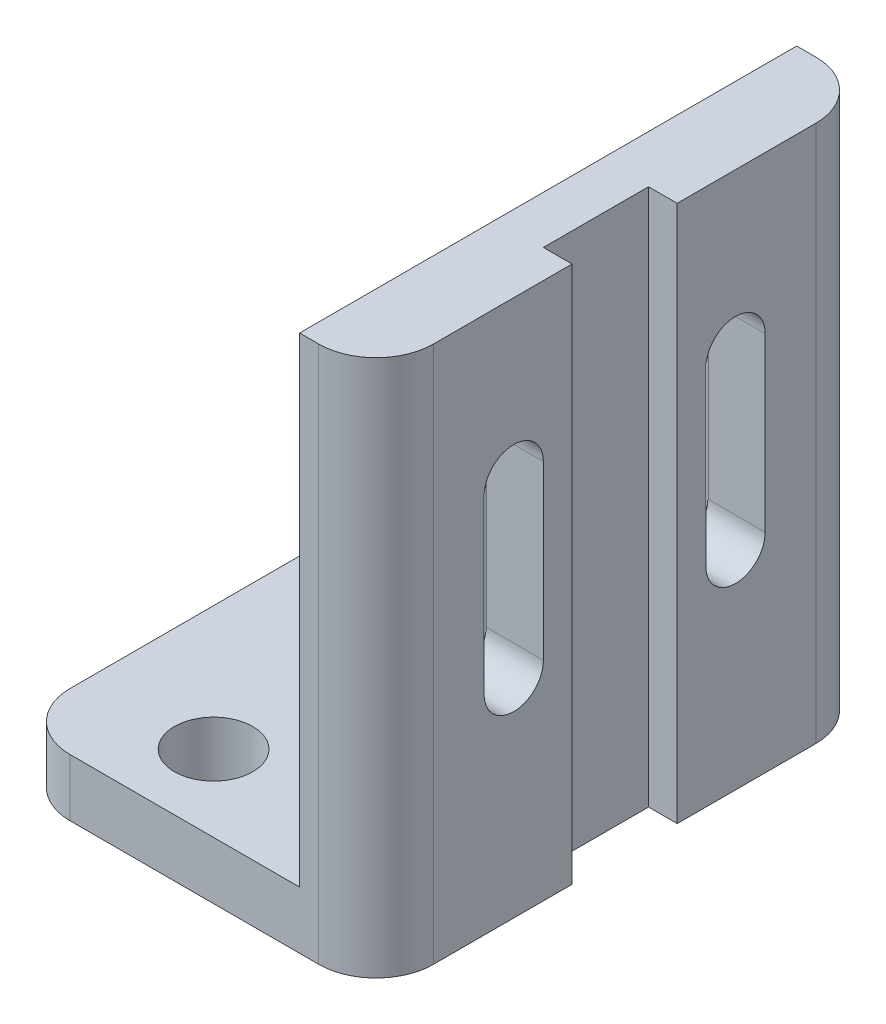
SolidWorks part; units mm, degrees
ref_plane "Front Plane" through (0, 0, 0) normal (0, 0, 1) x (1, 0, 0)
ref_plane "Top Plane" through (0, 0, 0) normal (0, 1, 0) x (1, 0, 0)
ref_plane "Right Plane" through (0, 0, 0) normal (1, 0, 0) x (0, 0, -1)
sketch "ProfileSketch1" plane through (0, 0, 0) normal (0, 0, 1) x (1, 0, 0)
  line L0 (0, 0) -> (19, 0)
  line L1 (19, 0) -> (19, 28.1)
  line L2 (19, 28.1) -> (15, 28.1)
  line L3 (15, 28.1) -> (15, 3)
  line L4 (15, 3) -> (0, 3)
  line L5 (0, 3) -> (0, 0)
  dimension "D1" = 28.1
  dimension "D3" = 3
  dimension "D4" = 4
  dimension "D2" = 15
extrude "Boss-Extrude1" add sketch "ProfileSketch1" along normal blind 26
sketch "BLTouchProbeMountHolesSketch2" plane through (0, 3, 0) normal (0, 1, 0) x (1, 0, 0)
  line L0 (15, -26) -> (0, -26) construction
  line L2 (15, -26) -> (15, 0) construction
  circle A0 centre (6.5, -4) radius 2.05
  circle A1 centre (6.5, -22) radius 2.05
  dimension "D4" = 4.1
  dimension "D1" = 18
  dimension "D2" = 4
  dimension "D3" = 8.5
extrude "BLTouchProbeMountHolesCut-Extrude1" cut sketch "BLTouchProbeMountHolesSketch2" against normal through all
sketch "ProbeSlidingMountSketch4" plane through (15, 0, 0) normal (-1, 0, 0) x (0, 0, 1)
  line L0 (26, 3) -> (0, 3) construction
  line L1 (0, 28.1) -> (0, 3) construction
  line L2 (26, 28.1) -> (26, 3) construction
  line L3 (5.65, 19.9) -> (5.65, 10.9)
  line L4 (8.75, 19.9) -> (8.75, 10.9)
  line L5 (17.25, 19.9) -> (17.25, 10.9)
  line L6 (20.35, 19.9) -> (20.35, 10.9)
  arc A0 (8.75, 19.9) -> (5.65, 19.9) centre (7.2, 19.9) ccw
  arc A1 (5.65, 10.9) -> (8.75, 10.9) centre (7.2, 10.9) ccw
  arc A2 (20.35, 19.9) -> (17.25, 19.9) centre (18.8, 19.9) ccw
  arc A3 (17.25, 10.9) -> (20.35, 10.9) centre (18.8, 10.9) ccw
  dimension "D1" = 3.1
  dimension "D2" = 9
  dimension "D3" = 7.9
  dimension "D4" = 11.6
  dimension "D5" = 7.2
  dimension "D6" = 7.2
fillet "Fillet1" radius 3 4 edges at (19, 14.05, 26) (19, 14.05, 0) (0, 1.5, 0) (0, 1.5, 26)
extrude "ProbeSlidingMountCut-Extrude3" cut sketch "ProbeSlidingMountSketch4" against normal through all
sketch "ProbeSlidingMountChannelSketch5" plane through (15, 0, 0) normal (-1, 0, 0) x (0, 0, 1)
  line L0 (7.2, 19.9) -> (7.2, 10.9) construction
  line L1 (10.4, 19.9) -> (10.4, 10.9)
  line L2 (4, 19.9) -> (4, 10.9)
  line L3 (18.8, 19.9) -> (18.8, 10.9) construction
  line L4 (22, 19.9) -> (22, 10.9)
  line L5 (15.6, 19.9) -> (15.6, 10.9)
  arc A0 (10.4, 19.9) -> (4, 19.9) centre (7.2, 19.9) ccw
  arc A1 (4, 10.9) -> (10.4, 10.9) centre (7.2, 10.9) ccw
  arc A2 (22, 19.9) -> (15.6, 19.9) centre (18.8, 19.9) ccw
  arc A3 (15.6, 10.9) -> (22, 10.9) centre (18.8, 10.9) ccw
  point P4 (7.2, 15.4)
  point P9 (18.8, 15.4)
  dimension "D1" = 6.4
extrude "ProbeSlidingMountChanelCut-Extrude4" cut sketch "ProbeSlidingMountChannelSketch5" against normal blind 1
sketch "CableChannelSketch1" plane through (19, 0, 0) normal (1, 0, 0) x (0, 0, -1)
  line L0 (-23, 28.1) -> (-3, 28.1) construction
  line L1 (-15.75, 28.1) -> (-10.25, 28.1)
  line L2 (-15.75, 28.1) -> (-15.75, 0)
  line L3 (-15.75, 0) -> (-10.25, 0)
  line L4 (-10.25, 28.1) -> (-10.25, 0)
  line L5 (-23, 0) -> (-3, 0) construction
  line L6 (-26, 0) -> (-26, 28.1) construction
  dimension "D1" = 5.5
  dimension "D2" = 10.25
extrude "CableCut-Extrude1" cut sketch "CableChannelSketch1" against normal blind 1.5
equation "\"ProbeMountHeight\"= \"ProbeMountDepth\" + \"ProbeMountUpperHeight\""
equation "\"D1@ProfileSketch1\" = \"ProbeMountHeight\""
equation "\"D1@Boss-Extrude1\"= \"ProbeBodyWidth\""
equation "\"M3HeatInsertHoleDiameter\"= 4.1mm'Spec"
equation "\"ProbeBodyDepth\"= 15mm"
equation "\"ProbeBodyWidth\"= 26mm"
equation "\"BLTouchProbeMountHoleDistance\"= 18mm"
equation "\"ProbeMountUpperHeight\"= \"M3ScrewButtonHeadHeight\" * 2 + \"M3ScrewDiameter\" * 5 + \"M3ScrewButtonHeadHeight\" * 2"
equation "\"D2@ProfileSketch1\"=\"ProbeBodyDepth\""
equation "\"D3@ProfileSketch1\"= \"ProbeMountDepth\""
equation "\"D4@ProfileSketch1\"=\"ProbeMountDepth\"+1mm"
equation "\"D1@BLTouchProbeMountHolesSketch2\" = \"BLTouchProbeMountHoleDistance\""
equation "\"D2@BLTouchProbeMountHolesSketch2\" =  ( \"ProbeBodyWidth\" - \"BLTouchProbeMountHoleDistance\" )  / 2"
equation "\"D4@BLTouchProbeMountHolesSketch2\" = \"M3HeatInsertHoleDiameter\""
equation "\"M3ScrewButtonHeadHeight\"= 2.4mm"
equation "\"D1@ProbeSlidingMountSketch4\" = \"M3ScrewDiameter\""
equation "\"D2@ProbeSlidingMountSketch4\" = 3mm * 3"
equation "\"M3ScrewDiameter\"= 3.1mm"
equation "\"D3@ProbeSlidingMountSketch4\" = \"M3ScrewButtonHeadHeight\" * 2 + \"M3ScrewDiameter\""
equation "\"ProbeMountDepth\"= 3mm"
equation "\"M3ScrewButtonHeadDiameter\"= 5.9mm"
equation "\"D1@ProbeSlidingMountChannelSketch5\"=\"M3ScrewButtonHeadDiameter\"+ .5mm"
equation "\"D2@CableChannelSketch1\" =  ( \"ProbeBodyWidth\" - \"BLTouchCableWidth\" )  / 2"
equation "\"BLTouchCableWidth\"= 5.5mm"
equation "\"D1@CableChannelSketch1\" = \"BLTouchCableWidth\""
equation "\"BLTouchCableThickness\"= 1.5mm"
equation "\"D1@CableCut-Extrude1\" = \"BLTouchCableThickness\""
equation "\"BLTouchMountingHoleOffsetFromBack\"= 8.5mm"
equation "\"D3@BLTouchProbeMountHolesSketch2\" = \"BLTouchMountingHoleOffsetFromBack\""
equation "\"ProbeMountHolesDistance\"=11.6"
equation "\"D5@ProbeSlidingMountSketch4\"=(\"ProbeBodyWidth\" - \"ProbeMountHolesDistance\")/2"
equation "\"D4@ProbeSlidingMountSketch4\"=\"ProbeMountHolesDistance\""
